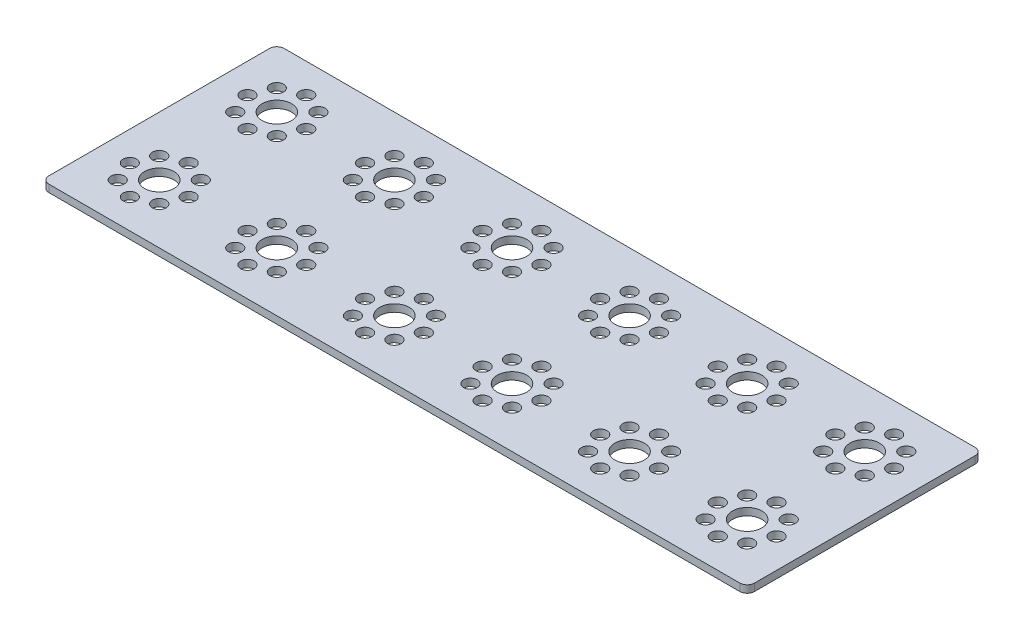
SolidWorks part; units mm, degrees
other "Defeature"
material "5052 Alloy"
ref_plane "Front Plane" through (0, 0, 0) normal (0, 0, 1) x (1, 0, 0)
ref_plane "Top Plane" through (0, 0, 0) normal (0, 1, 0) x (1, 0, 0)
ref_plane "Right Plane" through (0, 0, 0) normal (1, 0, 0) x (0, 0, -1)
sketch "Sketch1" plane through (0, 0, 0) normal (0, 1, 0) x (1, 0, 0)
  line L1 (-96, -32) -> (96, -32)
  line L2 (-96, -32) -> (-96, 32)
  line L3 (-96, 32) -> (96, 32)
  line L4 (96, -32) -> (96, 32)
  point P5 (-96, 0)
  point P7 (0, 32)
  dimension "D1" = 192
  dimension "D2" = 64
extrude "Extrude1" add sketch "Sketch1" along normal blind 2
sketch "Sketch2" plane through (0, 2, 0) normal (0, 1, 0) x (1, 0, 0)
  line L0 (96, 32) -> (-96, 32) construction
  line L1 (-96, -32) -> (96, -32) construction
  line L2 (0, 32) -> (0, -32) construction
  line L7 (-85.6569, 21.6569) -> (-74.3431, 10.3431) construction
  line L8 (-74.3431, 21.6569) -> (-85.6569, 10.3431) construction
  line L9 (-80, 16) -> (-80, 8) construction
  line L10 (-96, 32) -> (-96, -32) construction
  circle A0 centre (-80, 16) radius 4
  circle A1 centre (-80, 8) radius 1.85
  circle A2 centre (-80, 24) radius 1.85
  circle A3 centre (-88, 16) radius 1.85
  circle A4 centre (-72, 16) radius 1.85
  circle A5 centre (-74.3431, 21.6569) radius 1.85
  circle A6 centre (-85.6569, 21.6569) radius 1.85
  circle A7 centre (-74.3431, 10.3431) radius 1.85
  circle A8 centre (-85.6569, 10.3431) radius 1.85
  circle A9 centre (-80, 16) radius 8 construction
  point P10 (-80, 16)
  dimension "D3" = 8
  dimension "D4" = 3.7
  dimension "D5" = 16
  dimension "D1" = 16
  dimension "D2" = 16
  dimension "D6" = 45
extrude "Cut-Extrude1" cut sketch "Sketch2" against normal through all
pattern_linear "LPattern1" count 6 spacing 32 along (1, 0, 0) count 2 spacing 32 along (0, 0, 1) of "Cut-Extrude1"
fillet "Fillet1" radius 2 4 edges at (-96, 1, 32) (96, 1, 32) (96, 1, -32) (-96, 1, -32)
